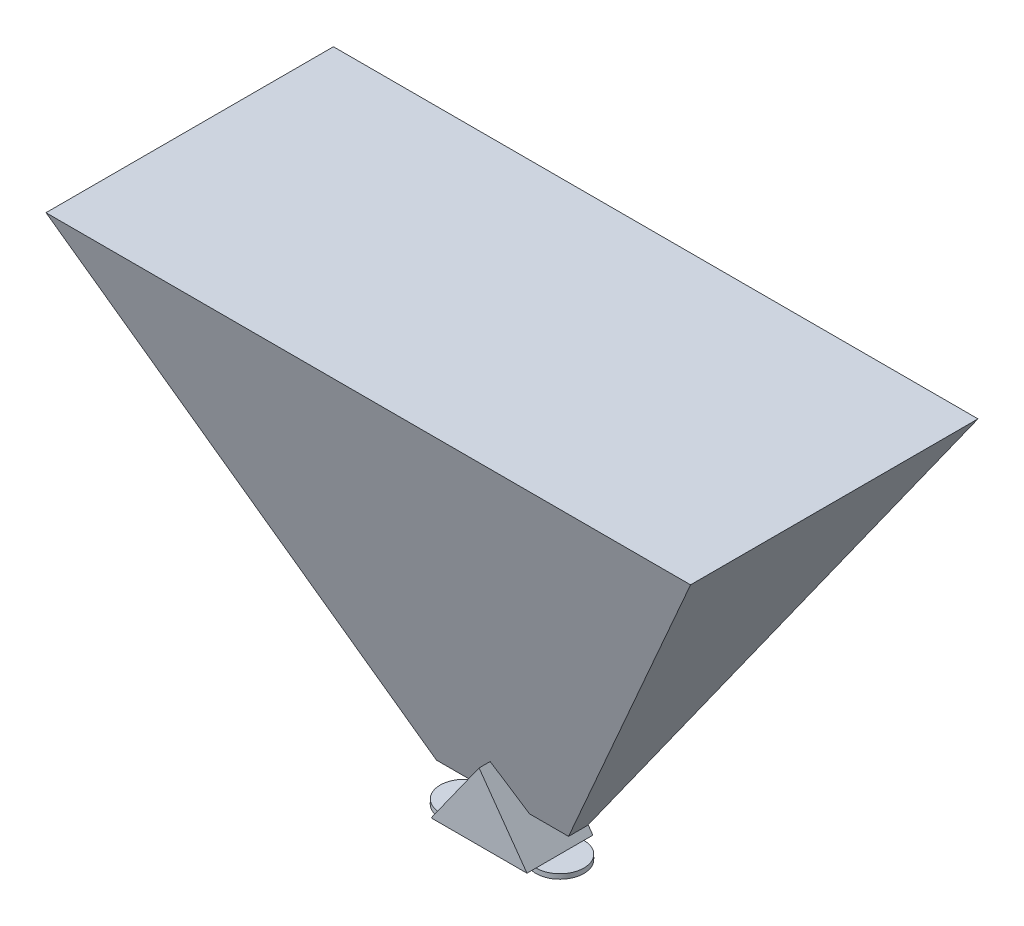
SolidWorks part; units mm, degrees
ref_plane "Front Plane" through (0, 0, 0) normal (0, 0, 1) x (1, 0, 0)
ref_plane "Top Plane" through (0, 0, 0) normal (0, 1, 0) x (1, 0, 0)
ref_plane "Right Plane" through (0, 0, 0) normal (1, 0, 0) x (0, 0, -1)
sketch "Sketch1" plane through (0, 0, 0) normal (0, 0, 1) x (1, 0, 0)
  line L0 (0, 0) -> (50.8, 0) construction
  line L1 (0, 0) -> (-43.2234, 80.8744) construction
  line L2 (0, 0) -> (50.8, 0)
  line L3 (50.8, 0) -> (-22.8097, -137.7297) construction
  line L4 (-1.6081, -2.2563) -> (43.6355, 61.2251) construction
  line L5 (49.083, 2.4091) -> (-0.222, 71.5891) construction
  line L6 (25.4, 0) -> (25.4, 35.6388) construction
  line L7 (25.4, 35.6388) -> (0, 0)
  line L8 (25.4, 35.6388) -> (50.8, 0)
  line L9 (0, 0) -> (-92.8473, 0) construction
  dimension "D1" = 50.8
  dimension "D2" = 63.6
  dimension "D3" = 63.6
  dimension "D4" = 90
extrude "Boss-Extrude1" add sketch "Sketch1" along normal mid plane 152.4
ref_plane "Plane1" through (25.4, 0, 0) normal (1, 0, 0) x (0, 0, -1)
ref_plane "Plane2" through (50.8, 0, 0) normal (1, 0, 0) x (0, 0, -1)
sketch "Sketch3" plane through (0, 0, 0) normal (1, 0, 0) x (0, 0, -1)
  line L0 (0, 0) -> (-11.5798, 35.6388) construction
  line L1 (76.2, 35.6388) -> (-76.2, 35.6388) construction
  line L2 (0, 0) -> (0, 35.6388) construction
  line L3 (0, 0) -> (11.5798, 35.6388) construction
  dimension "D1" = 18
  dimension "D2" = 18
sketch "Sketch7" plane through (0, 0, 0) normal (1, 0, 0) x (0, 0, -1)
  line L0 (76.2, 304.8) -> (99.0355, 304.8)
  line L1 (-76.2, 0) -> (76.2, 0)
  line L2 (-76.2, 0) -> (-76.2, 304.8)
  line L3 (-76.2, 304.8) -> (76.2, 304.8)
  line L4 (76.2, 0) -> (76.2, 304.8)
  line L5 (99.0355, 304.8) -> (0, 0)
  line L6 (0, 0) -> (-99.0355, 304.8)
  line L7 (0, 304.8) -> (0, 0) construction
  line L8 (5.0358, 15.4987) -> (-5.0358, 15.4987)
  dimension "D1" = 18
  dimension "D2" = 18
  dimension "D3" = 304.8
extrude "Boss-Extrude6" add sketch "Sketch7" along normal blind 203.2 and the other way blind 152.4 contours L7 L3 L6 L8 | L3 L7 L8 L5
sketch "Sketch8" plane through (0, 0, 76.2) normal (0, 0, 1) x (1, 0, 0)
  line L0 (0, 0) -> (-148.5224, 239.4254) construction
  line L1 (0, -190211.3033) -> (0, 190246.9421) construction
  line L2 (50.8, 0) -> (50.8, 304.8) construction
  line L3 (50.8, -111.76) -> (50.8, 111.76) construction
  line L4 (-152.4, 304.8) -> (203.2, 304.8) construction
  line L5 (50.8, 0) -> (254.9392, 329.1145) construction
  line L6 (-152.4, 245.6763) -> (-152.4, 15.4987)
  line L7 (-152.4, 234.5195) -> (-152.4, 304.8) construction
  line L8 (-152.4, 15.4987) -> (-9.6143, 15.4987)
  line L9 (-152.4, 15.4987) -> (11.046, 15.4987) construction
  line L10 (-9.6143, 15.4987) -> (-145.4791, 234.5195)
  line L11 (-152.4, 234.5195) -> (203.2, 234.5195) construction
  line L12 (-145.4791, 234.5195) -> (-152.4, 234.5195)
  line L13 (196.2649, 234.5195) -> (203.2, 234.5195)
  line L14 (203.2, 234.5195) -> (203.2, 15.4987)
  line L15 (203.2, 15.4987) -> (60.4133, 15.4987)
  line L16 (39.754, 15.4987) -> (203.2, 15.4987) construction
  line L17 (60.4133, 15.4987) -> (196.2649, 234.5195)
  dimension "D1" = 31.813
  dimension "D2" = 31.81
extrude "Cut-Extrude1" cut sketch "Sketch8" against normal through all contours L10 L12 L6 L8 | L17 L15 L14 L13
sketch "Sketch9" plane through (203.2, 0, 0) normal (1, 0, 0) x (0, 0, -1)
  line L1 (-76.2, 234.5195) -> (76.2, 234.5195)
  line L2 (-76.2, 234.5195) -> (-76.2, 304.8)
  line L3 (-76.2, 304.8) -> (76.2, 304.8)
  line L4 (76.2, 234.5195) -> (76.2, 304.8)
extrude "Cut-Extrude2" cut sketch "Sketch9" against normal through all
sketch "Sketch10" plane through (0, 0, 0) normal (0, -1, 0) x (-1, 0, 0)
  line L0 (-50.8, 76.2) -> (-50.8, -76.2) construction
  circle A0 centre (0, 0) radius 12.7
  circle A1 centre (-50.8, 0) radius 12.7
  dimension "D1" = 25.4
  dimension "D2" = 25.4
extrude "Boss-Extrude7" add sketch "Sketch10" along normal blind 2.54
sketch "Sketch11" plane through (50.8, 0, 0) normal (1, 0, 0) x (0, 0, -1)
  line L0 (-12.7, 0) -> (-76.2, 0) construction
  line L1 (-76.2, 35.6388) -> (-17.4677, 35.6388)
  line L2 (-76.2, 35.6388) -> (-76.2, 0)
  line L3 (-76.2, 0) -> (-17.4677, 0)
  line L4 (-17.4677, 35.6388) -> (-17.4677, 0)
  line L5 (0, 35.6388) -> (0, 0) construction
  line L6 (76.2, 0) -> (17.4677, 0)
  line L7 (76.2, 35.6388) -> (76.2, 0)
  line L8 (76.2, 35.6388) -> (17.4677, 35.6388)
  line L9 (17.4677, 35.6388) -> (17.4677, 0)
extrude "Cut-Extrude3" cut sketch "Sketch11" against normal through all
